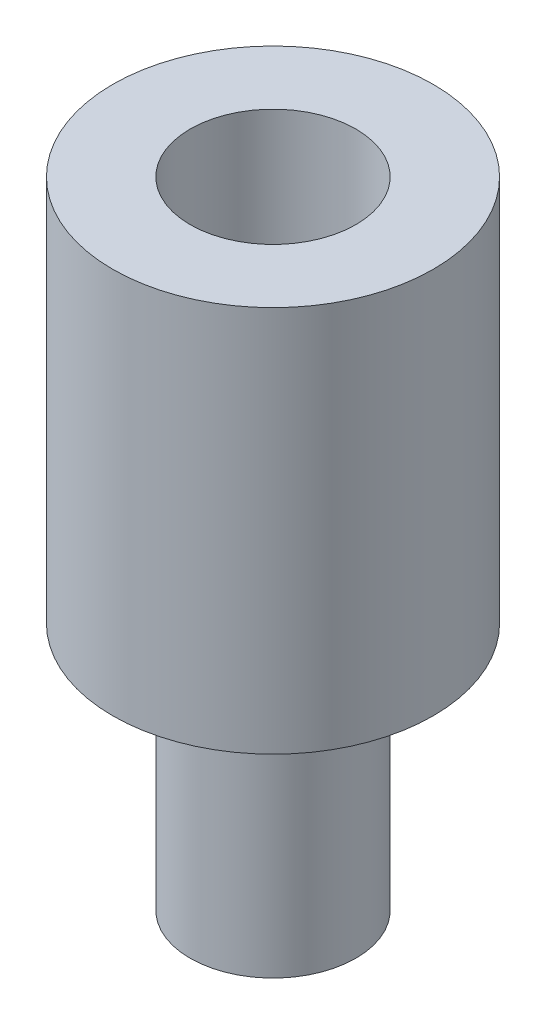
SolidWorks part; units mm, degrees
ref_plane "Front Plane" through (0, 0, 0) normal (0, 0, 1) x (1, 0, 0)
ref_plane "Top Plane" through (0, 0, 0) normal (0, 1, 0) x (1, 0, 0)
ref_plane "Right Plane" through (0, 0, 0) normal (1, 0, 0) x (0, 0, -1)
sketch "Sketch1" plane through (0, 0, 0) normal (0, 1, 0) x (1, 0, 0)
  circle A0 centre (0, 0) radius 1.5 construction
  circle A1 centre (0, 0) radius 2.9
  dimension "D1" = 3
  dimension "D2" = 5.8
extrude "Boss-Extrude1" add sketch "Sketch1" along normal blind 7
sketch "Sketch2" plane through (0, 0, 0) normal (0, -1, 0) x (1, 0, 0)
  circle A0 centre (0, 0) radius 1.5
  dimension "D1" = 3
extrude "Boss-Extrude2" add sketch "Sketch2" along normal blind 4.5
sketch "Sketch3" plane through (0, 7, 0) normal (0, 1, 0) x (1, 0, 0)
  circle A0 centre (0, 0) radius 1.5
  dimension "D1" = 3
extrude "Cut-Extrude1" cut sketch "Sketch3" against normal blind 4.5
